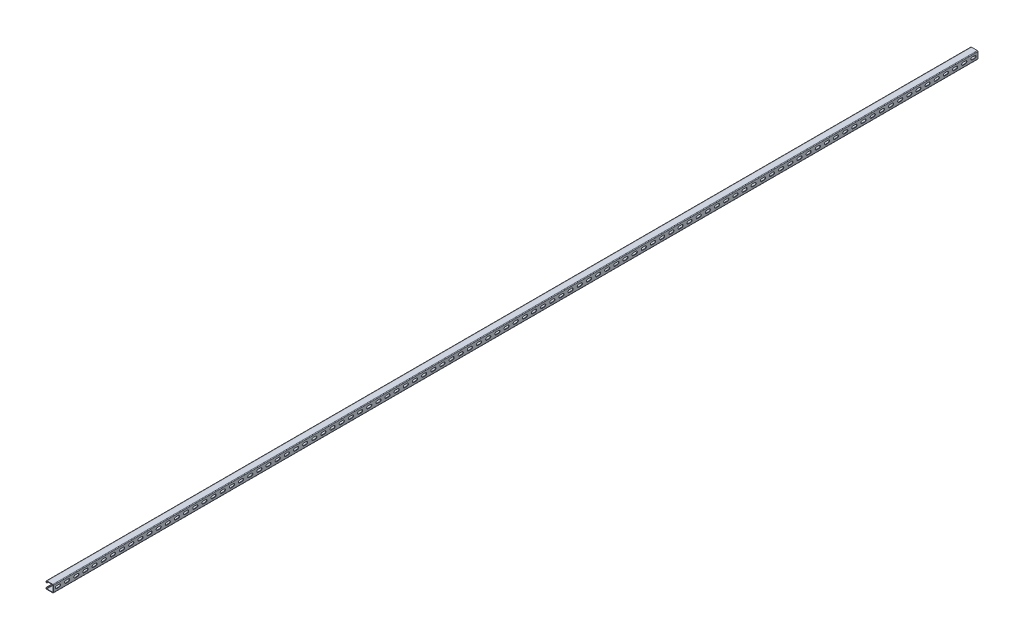
SolidWorks part; units mm, degrees
material "AISI 304"
ref_plane "Front Plane" through (0, 0, 0) normal (0, 0, 1) x (1, 0, 0)
ref_plane "Top Plane" through (0, 0, 0) normal (0, 1, 0) x (1, 0, 0)
ref_plane "Right Plane" through (0, 0, 0) normal (1, 0, 0) x (0, 0, -1)
sketch "Sketch1" plane through (0, 0, 0) normal (0, 0, 1) x (1, 0, 0)
  line L0 (0, 0) -> (-41.275, 0) construction
  line L3 (-41.275, 20.6375) -> (0, 20.6375) construction
  line L4 (-41.275, 20.6375) -> (-41.275, -20.6375) construction
  line L5 (-41.275, -20.6375) -> (0, -20.6375) construction
  line L6 (0, 20.6375) -> (0, -20.6375) construction
  line L7 (-36.2267, 20.6375) -> (-3.4607, 20.6375)
  line L8 (0, 17.1767) -> (0, -17.1767)
  line L9 (-2.794, -17.1767) -> (-2.794, 17.1767)
  line L10 (-3.4608, 17.8435) -> (-36.2267, 17.8435)
  line L11 (-41.275, 15.5892) -> (-41.275, 14.5732)
  line L12 (-37.8142, 11.1125) -> (-35.5346, 11.1125)
  line L14 (-35.5346, 13.9065) -> (-37.8142, 13.9065)
  line L15 (-38.481, 14.5732) -> (-38.481, 15.5892)
  line L16 (-38.481, -14.5733) -> (-38.481, -15.5893)
  line L17 (-35.5346, -13.9065) -> (-37.8142, -13.9065)
  line L18 (-37.8142, -11.1125) -> (-35.5346, -11.1125)
  line L19 (-41.275, -15.5893) -> (-41.275, -14.5733)
  line L20 (-3.4607, -17.8435) -> (-36.2267, -17.8435)
  line L21 (-36.2267, -20.6375) -> (-3.4607, -20.6375)
  line L22 (-2.794, -20.6375) -> (-2.794, 20.6375) construction
  arc A1 (0, 17.1767) -> (-3.4607, 20.6375) centre (-3.4607, 17.1767) ccw
  arc A2 (-2.794, 17.1767) -> (-3.4608, 17.8435) centre (-3.4607, 17.1767) ccw
  arc A4 (-36.2267, 20.6375) -> (-41.275, 15.5892) centre (-36.2267, 15.5892) ccw
  arc A5 (-41.275, 14.5732) -> (-37.8142, 11.1125) centre (-37.8142, 14.5732) ccw
  arc A6 (-35.5346, 11.1125) -> (-35.5346, 13.9065) centre (-35.5346, 12.5095) ccw
  arc A7 (-37.8142, 13.9065) -> (-38.481, 14.5732) centre (-37.8142, 14.5732) cw
  arc A8 (-38.481, 15.5892) -> (-36.2267, 17.8435) centre (-36.2267, 15.5892) cw
  arc A9 (-38.481, -15.5893) -> (-36.2267, -17.8435) centre (-36.2267, -15.5893) ccw
  arc A10 (-37.8142, -13.9065) -> (-38.481, -14.5733) centre (-37.8142, -14.5733) ccw
  arc A11 (-35.5346, -11.1125) -> (-35.5346, -13.9065) centre (-35.5346, -12.5095) cw
  arc A12 (-41.275, -14.5733) -> (-37.8142, -11.1125) centre (-37.8142, -14.5733) cw
  arc A13 (-36.2267, -20.6375) -> (-41.275, -15.5893) centre (-36.2267, -15.5893) cw
  arc A14 (-2.794, -17.1767) -> (-3.4607, -17.8435) centre (-3.4607, -17.1767) cw
  arc A15 (0, -17.1767) -> (-3.4607, -20.6375) centre (-3.4607, -17.1767) cw
  point P24 (0, 20.6375)
  point P65 (-2.794, 0)
  dimension "D1" = 3.4608
  dimension "D2" = 5.0482
  dimension "D3" = 3.4608
  dimension "Ht." = 41.275
  dimension "Wd." = 41.275
  dimension "Thk." = 2.794
  dimension "D4" = 9.525
  dimension "D5" = 7.1374
extrude "Boss-Extrude1" add sketch "Sketch1" against normal blind 5130.8
sketch "Sketch3" plane through (0, 0, 0) normal (1, 0, 0) x (0, 0, -1)
  line L0 (0, 0) -> (5130.8, 0) construction
  point P2 (101.6, 0)
  point P3 (5029.2, 0)
  dimension "D1" = 101.6
  dimension "D2" = 101.6
  dimension "D3" = 5130.8
sketch "Sketch2" plane through (0, 0, 0) normal (1, 0, 0) x (0, 0, -1)
  line L0 (18.2562, 0) -> (32.5437, 0) construction
  line L1 (18.2562, 7.1437) -> (32.5437, 7.1437)
  line L2 (18.2562, -7.1437) -> (32.5437, -7.1437)
  line L3 (18.2562, 0) -> (0, 0) construction
  line L4 (25.4, 0) -> (76.2, 0) construction
  line L5 (0, -17.1767) -> (0, 17.1767) construction
  arc A0 (18.2562, 7.1437) -> (18.2562, -7.1437) centre (18.2562, 0) ccw
  arc A1 (32.5437, -7.1437) -> (32.5437, 7.1437) centre (32.5437, 0) ccw
  point P3 (25.4, 0)
  dimension "Hole to End" = 11.1125
  dimension "D2" = 25.4
extrude "Cut-Extrude1" cut sketch "Sketch2" against normal up to vertex (2.794 mm away) up to point (-2.794, 0, 0)
pattern_linear "LPattern1" count 101 spacing 50.8 along (0, 0, -1) of "Cut-Extrude1"
sketch "Sketch4" plane through (0, 0, 0) normal (1, 0, 0) x (0, 0, -1)
  circle A0 centre (32.5437, 0) radius 9.525
  circle A1 centre (69.5329, -2.346) radius 9.525
  circle A2 centre (32.5437, 0) radius 4.7625
  circle A3 centre (69.5329, -2.346) radius 4.7625
  circle A4 centre (69.5329, -2.346) radius 12.7
  dimension "D1" = 19.05
  dimension "D2" = 19.05
  dimension "D3" = 9.525
  dimension "D4" = 25.4
equation "\"D1@LPattern1\" = \"Slot Ctr.@Sketch2\""
equation "\"Hole Count@LPattern1\" = \"Lg.@Boss-Extrude1\" / \"D1@LPattern1\""
equation "\"D3@Sketch3\" = \"Lg.@Boss-Extrude1\""
